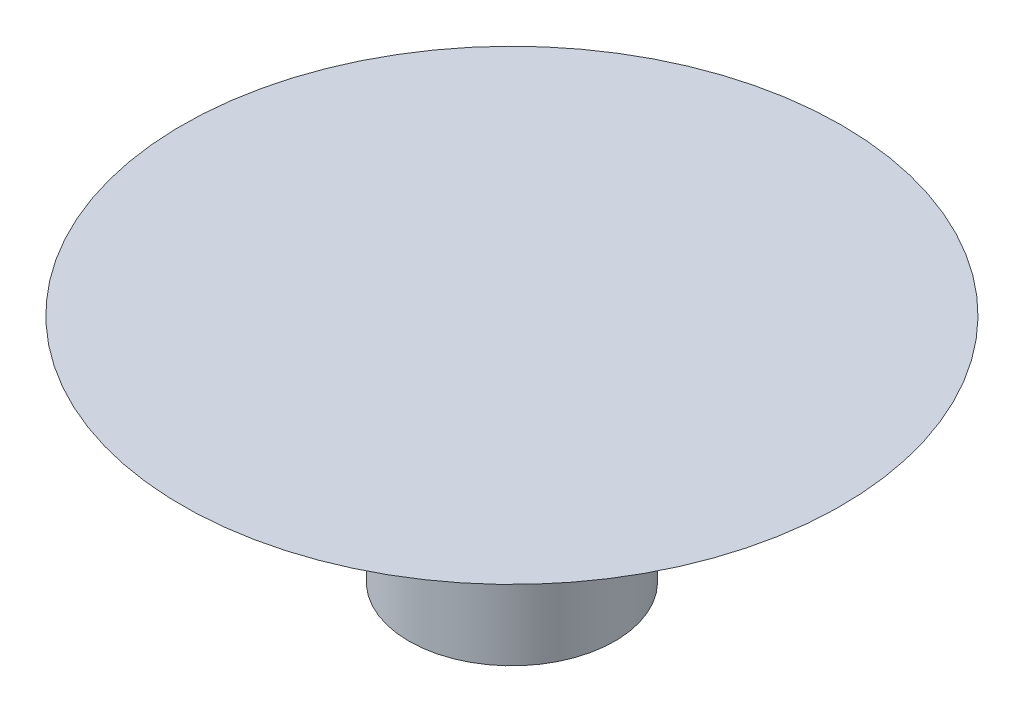
SolidWorks part; units mm, degrees
ref_plane "Спереди" through (0, 0, 0) normal (0, 0, 1) x (1, 0, 0)
ref_plane "Сверху" through (0, 0, 0) normal (0, 1, 0) x (1, 0, 0)
ref_plane "Справа" through (0, 0, 0) normal (1, 0, 0) x (0, 0, -1)
sketch "Эскиз2" plane through (0, 0, 0) normal (0, 1, 0) x (1, 0, 0)
  circle A0 centre (0, 0) radius 1.25
  dimension "D1" = 2.5
extrude "Бобышка-Вытянуть1" add sketch "Эскиз2" against normal blind 1.8
sketch "Эскиз4" plane through (0, 0, 0) normal (0, 0, 1) x (1, 0, 0)
  line L0 (0, 0) -> (0, 1)
  line L2 (0, 0) -> (1.25, 0)
  line L3 (1.25, 0) -> (2.0418, 0)
  line L4 (2.6546, 0.2858) -> (2.7743, 0.4285)
  line L5 (0, 1) -> (4, 1)
  arc A0 (2.0418, 0) -> (2.6546, 0.2858) centre (2.0418, 0.8) ccw
  arc A1 (4, 1) -> (2.7743, 0.4285) centre (4, -0.6) ccw
  dimension "D1" = 0.8
  dimension "D4" = 1.6
  dimension "D2" = 4
  dimension "D3" = 130
revolve "Повернуть1" add sketch "Эскиз4" angle 360 about L0
sketch "Эскиз ориентации" plane through (0, 1, 0) normal (0, 1, 0) x (1, 0, 0)
  circle A0 centre (0, 0) radius 4 construction
  circle A1 centre (0, 0) radius 4
  point P3 (0, 0)
other "Инструмент формы1"
